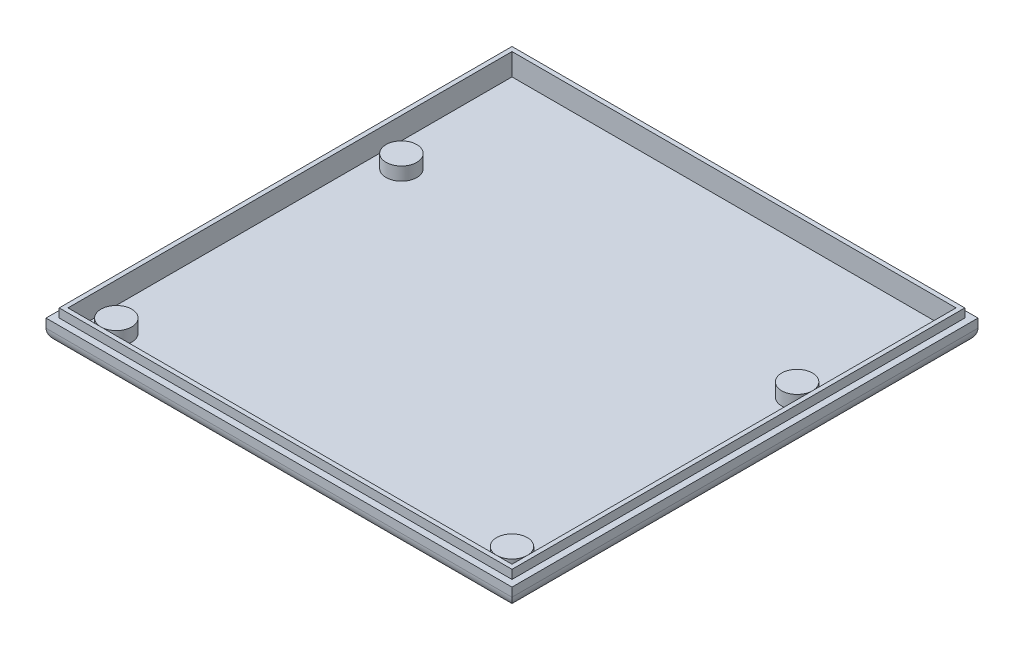
SolidWorks part; units mm, degrees
ref_plane "Front Plane" through (0, 0, 0) normal (0, 0, 1) x (1, 0, 0)
ref_plane "Top Plane" through (0, 0, 0) normal (0, 1, 0) x (1, 0, 0)
ref_plane "Right Plane" through (0, 0, 0) normal (1, 0, 0) x (0, 0, -1)
sketch "Sketch4" plane through (0, 0, 0) normal (0, 1, 0) x (1, 0, 0)
  line L1 (-100.6895, 8.5392) -> (5.3105, 8.5392)
  line L2 (-100.6895, 8.5392) -> (-100.6895, -97.4608)
  line L3 (-100.6895, -97.4608) -> (5.3105, -97.4608)
  line L4 (5.3105, 8.5392) -> (5.3105, -97.4608)
  line L5 (-100.6895, 8.5392) -> (5.3105, -97.4608) construction
  line L6 (-100.6895, -97.4608) -> (5.3105, 8.5392) construction
  point P0 (-47.6895, -44.4608)
  dimension "D1" = 106
  dimension "D2" = 106
extrude "Boss-Extrude3" add sketch "Sketch4" along normal blind 5
sketch "Sketch6" plane through (0, 5, 0) normal (0, 1, 0) x (1, 0, 0)
  line L1 (-98.1895, 6.0392) -> (2.8105, 6.0392)
  line L2 (-98.1895, 6.0392) -> (-98.1895, -94.9608)
  line L3 (-98.1895, -94.9608) -> (2.8105, -94.9608)
  line L4 (2.8105, 6.0392) -> (2.8105, -94.9608)
  line L5 (-98.1895, 6.0392) -> (2.8105, -94.9608) construction
  line L6 (-98.1895, -94.9608) -> (2.8105, 6.0392) construction
  point P0 (-47.6895, -44.4608)
  dimension "D1" = 101
  dimension "D2" = 101
extrude "Cut-Extrude2" cut sketch "Sketch6" against normal blind 3
ref_plane "Plane1" through (0, 2, 0) normal (0, 1, 0) x (1, 0, 0)
sketch "Sketch7" plane through (0, 2, 0) normal (0, 1, 0) x (1, 0, 0)
  circle A1 centre (-92.6895, -24.6108) radius 3.5
  circle A2 centre (-92.6895, -89.4608) radius 3.5
  circle A3 centre (-2.6895, -89.4608) radius 3.5
  circle A4 centre (-2.6895, -24.6108) radius 3.5
  point P2 (0, 0)
  point P3 (-2.6895, -24.6108)
  point P6 (-92.6895, -24.6108)
  point P7 (-87.8419, -89.706)
  point P12 (0, 0)
  point P13 (-92.6895, -89.4608)
  point P14 (-2.6895, -89.4608)
  dimension "D2" = 7
  dimension "D3" = 7
  dimension "D4" = 7
  dimension "D5" = 7
extrude "Boss-Extrude4" add sketch "Sketch7" along normal blind 3
fillet "Fillet1" radius 3 4 edges at (-47.6895, 0, 97.4608) (-100.6895, 0, 44.4608) (-47.6895, 0, -8.5392) (5.3105, 0, 44.4608)
sketch "Sketch10" plane through (0, 5, 0) normal (0, 1, 0) x (1, 0, 0)
  line L0 (-100.6895, 8.5392) -> (5.3105, -97.4608) construction
  line L1 (-99.1895, 7.0392) -> (3.8105, 7.0392)
  line L2 (-99.1895, 7.0392) -> (-99.1895, -95.9608)
  line L3 (-99.1895, -95.9608) -> (3.8105, -95.9608)
  line L4 (3.8105, 7.0392) -> (3.8105, -95.9608)
  line L5 (-99.1895, 7.0392) -> (3.8105, -95.9608) construction
  line L6 (-99.1895, -95.9608) -> (3.8105, 7.0392) construction
  line L8 (-98.1895, 6.0392) -> (2.8105, 6.0392)
  line L9 (-98.1895, 6.0392) -> (-98.1895, -94.9608)
  line L10 (-98.1895, -94.9608) -> (2.8105, -94.9608)
  line L11 (2.8105, 6.0392) -> (2.8105, -94.9608)
  line L12 (-98.1895, 6.0392) -> (2.8105, -94.9608) construction
  line L13 (-98.1895, -94.9608) -> (2.8105, 6.0392) construction
  point P0 (-47.6895, -44.4608)
  point P8 (-47.6895, -44.4608)
  dimension "D1" = 103
extrude "Boss-Extrude5" add sketch "Sketch10" along normal blind 2
